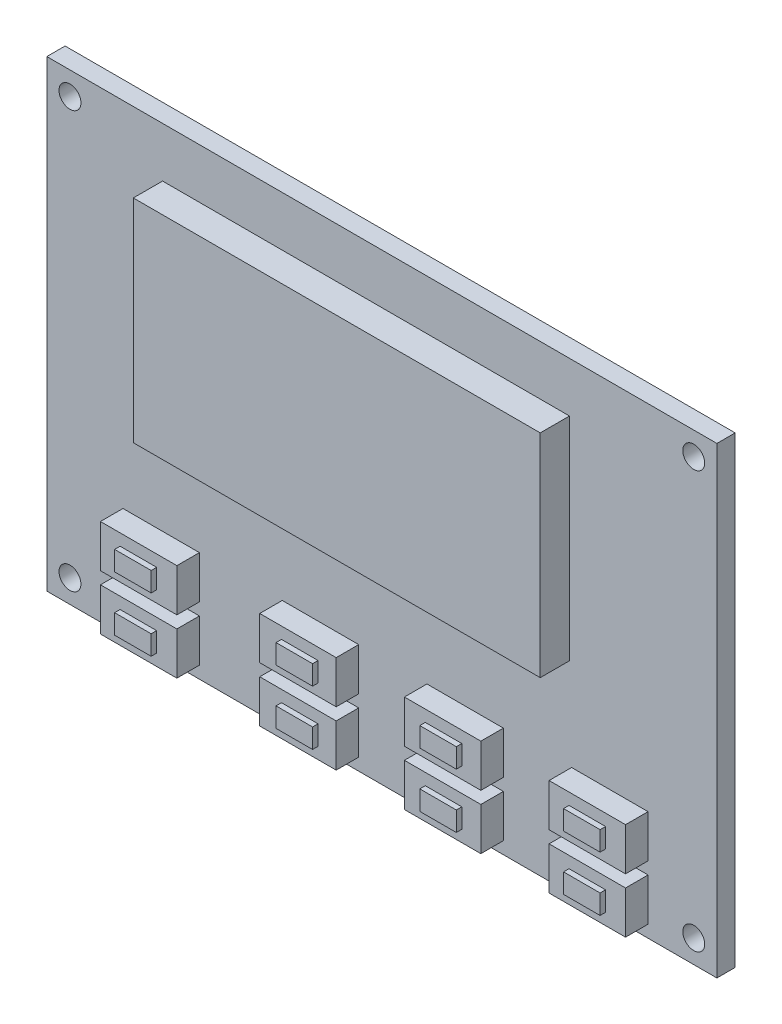
SolidWorks part; units mm, degrees
ref_plane "Front Plane" through (0, 0, 0) normal (0, 0, 1) x (1, 0, 0)
ref_plane "Top Plane" through (0, 0, 0) normal (0, 1, 0) x (1, 0, 0)
ref_plane "Right Plane" through (0, 0, 0) normal (1, 0, 0) x (0, 0, -1)
sketch "Sketch1" plane through (0, 0, 0) normal (0, 0, 1) x (1, 0, 0)
  line L0 (24.7, 17.1) -> (26.5, 17.1) construction
  line L1 (-27.5, 19) -> (27.5, 19)
  line L2 (-27.5, 19) -> (-27.5, -19)
  line L3 (-27.5, -19) -> (27.5, -19)
  line L4 (27.5, 19) -> (27.5, -19)
  line L5 (-27.5, 19) -> (27.5, -19) construction
  line L6 (-27.5, -19) -> (27.5, 19) construction
  line L7 (25.6, 18) -> (25.6, 16.2) construction
  line L8 (0, 19) -> (0, -19) construction
  line L9 (-27.5, 0) -> (27.5, 0) construction
  circle A0 centre (25.6, 17.1) radius 0.9
  circle A1 centre (-25.6, 17.1) radius 0.9
  circle A2 centre (25.6, -17.1) radius 0.9
  circle A3 centre (-25.6, -17.1) radius 0.9
  point P0 (0, 0)
  dimension "D3" = 1
  dimension "D5" = 1.8
  dimension "D1" = 38
  dimension "D2" = 55
  dimension "D4" = 1
extrude "Boss-Extrude1" add sketch "Sketch1" along normal mid plane 1.5
sketch "Sketch2" plane through (0, 0, 0.75) normal (0, 0, 1) x (1, 0, 0)
  line L0 (27.5, 19) -> (-27.5, 19) construction
  line L1 (-18, 14.9) -> (15.4, 14.9)
  line L2 (-18, 14.9) -> (-18, -2.5)
  line L3 (-18, -2.5) -> (15.4, -2.5)
  line L4 (15.4, 14.9) -> (15.4, -2.5)
  line L5 (27.5, -19) -> (27.5, 19) construction
  line L6 (-27.5, 19) -> (-27.5, -19) construction
  line L7 (-27.5, -19) -> (27.5, -19) construction
  dimension "D1" = 4.1
  dimension "D2" = 12.1
  dimension "D3" = 9.5
  dimension "D4" = 16.5
extrude "Boss-Extrude2" add sketch "Sketch2" along normal mid plane 4.8
sketch "Sketch4" plane through (0, 0, 0.75) normal (0, 0, 1) x (1, 0, 0)
  line L0 (-27.5, 19) -> (-27.5, -19) construction
  line L1 (21.85, -18) -> (15.575, -18)
  line L2 (21.85, -18) -> (21.85, -14.5)
  line L3 (21.85, -14.5) -> (15.575, -14.5)
  line L4 (15.575, -18) -> (15.575, -14.5)
  line L5 (-21.25, -14.5) -> (-14.975, -14.5)
  line L6 (-21.25, -14.5) -> (-21.25, -18)
  line L7 (-21.25, -18) -> (-14.975, -18)
  line L8 (-14.975, -14.5) -> (-14.975, -18)
  line L9 (27.5, -19) -> (27.5, 19) construction
  line L10 (-27.5, -19) -> (27.5, -19) construction
  line L11 (9.975, -14.5) -> (3.7, -14.5)
  line L12 (9.975, -14.5) -> (9.975, -18)
  line L13 (9.975, -18) -> (3.7, -18)
  line L14 (3.7, -14.5) -> (3.7, -18)
  line L15 (-1.9, -14.5) -> (-8.175, -14.5)
  line L16 (-1.9, -14.5) -> (-1.9, -18)
  line L17 (-1.9, -18) -> (-8.175, -18)
  line L18 (-8.175, -14.5) -> (-8.175, -18)
  line L19 (-21.25, -10) -> (-21.25, -13.5)
  line L20 (-21.25, -10) -> (-14.975, -10)
  line L21 (-14.975, -10) -> (-14.975, -13.5)
  line L22 (-21.25, -13.5) -> (-14.975, -13.5)
  line L23 (-1.9, -10) -> (-1.9, -13.5)
  line L24 (-1.9, -10) -> (-8.175, -10)
  line L25 (-8.175, -10) -> (-8.175, -13.5)
  line L26 (-1.9, -13.5) -> (-8.175, -13.5)
  line L27 (9.975, -10) -> (9.975, -13.5)
  line L28 (9.975, -10) -> (3.7, -10)
  line L29 (3.7, -10) -> (3.7, -13.5)
  line L30 (9.975, -13.5) -> (3.7, -13.5)
  line L31 (21.85, -13.5) -> (21.85, -10)
  line L32 (21.85, -13.5) -> (15.575, -13.5)
  line L33 (15.575, -13.5) -> (15.575, -10)
  line L34 (21.85, -10) -> (15.575, -10)
  dimension "D1" = 6.25
  dimension "D2" = 5.65
  dimension "D3" = 1
  dimension "D4" = 5.6
  dimension "D5" = 5.6
  dimension "D6" = 6.8
  dimension "D7" = 3.5
  dimension "D8" = 2
  dimension "D9" = 1
extrude "Boss-Extrude3" add sketch "Sketch4" along normal mid plane 3.7
sketch "Sketch6" plane through (0, 0, 2.6) normal (0, 0, 1) x (1, 0, 0)
  line L0 (18.7125, -14.5) -> (18.7125, -18) construction
  line L1 (17.2125, -15.45) -> (20.2125, -15.45)
  line L2 (17.2125, -15.45) -> (17.2125, -17.05)
  line L3 (17.2125, -17.05) -> (20.2125, -17.05)
  line L4 (20.2125, -15.45) -> (20.2125, -17.05)
  line L5 (17.2125, -15.45) -> (20.2125, -17.05) construction
  line L6 (17.2125, -17.05) -> (20.2125, -15.45) construction
  line L7 (15.575, -14.5) -> (21.85, -14.5) construction
  line L8 (21.85, -18) -> (15.575, -18) construction
  line L9 (21.85, -16.25) -> (15.575, -16.25) construction
  line L10 (21.85, -14.5) -> (21.85, -18) construction
  line L11 (15.575, -18) -> (15.575, -14.5) construction
  line L12 (5.4125, -17.05) -> (8.4125, -17.05)
  line L13 (8.4125, -15.45) -> (8.4125, -17.05)
  line L14 (5.4125, -15.45) -> (8.4125, -15.45)
  line L15 (5.4125, -15.45) -> (5.4125, -17.05)
  line L16 (-6.3875, -17.05) -> (-3.3875, -17.05)
  line L17 (-3.3875, -15.45) -> (-3.3875, -17.05)
  line L18 (-6.3875, -15.45) -> (-3.3875, -15.45)
  line L19 (-6.3875, -15.45) -> (-6.3875, -17.05)
  line L20 (5.4125, -12.55) -> (8.4125, -12.55)
  line L21 (8.4125, -10.95) -> (8.4125, -12.55)
  line L22 (5.4125, -10.95) -> (8.4125, -10.95)
  line L23 (5.4125, -10.95) -> (5.4125, -12.55)
  line L24 (-6.3875, -12.55) -> (-3.3875, -12.55)
  line L25 (-3.3875, -10.95) -> (-3.3875, -12.55)
  line L26 (-6.3875, -10.95) -> (-3.3875, -10.95)
  line L27 (-6.3875, -10.95) -> (-6.3875, -12.55)
  line L28 (17.2125, -12.55) -> (20.2125, -12.55)
  line L29 (20.2125, -10.95) -> (20.2125, -12.55)
  line L30 (17.2125, -10.95) -> (20.2125, -10.95)
  line L31 (17.2125, -10.95) -> (17.2125, -12.55)
  line L32 (-14.975, -13.5) -> (-14.975, -14.5) construction
  line L33 (-19.6375, -17.05) -> (-16.6375, -17.05)
  line L34 (-19.6375, -17.05) -> (-19.6375, -15.45)
  line L35 (-19.6375, -15.45) -> (-16.6375, -15.45)
  line L36 (-16.6375, -17.05) -> (-16.6375, -15.45)
  line L37 (-21.25, -13.5) -> (-21.25, -14.5) construction
  line L38 (-14.975, -14) -> (-21.25, -14) construction
  line L39 (-19.6375, -12.55) -> (-16.6375, -12.55)
  line L40 (-16.6375, -10.95) -> (-16.6375, -12.55)
  line L41 (-19.6375, -10.95) -> (-16.6375, -10.95)
  line L42 (-19.6375, -10.95) -> (-19.6375, -12.55)
  point P0 (18.7125, -16.25)
  dimension "D1" = 1.6
  dimension "D2" = 3
  dimension "D3" = 3
  dimension "D5" = 4.5
  dimension "D6" = 8.8
  dimension "D7" = 10.25
  dimension "D4" = 2
extrude "Boss-Extrude4" add sketch "Sketch6" along normal mid plane 0.9
